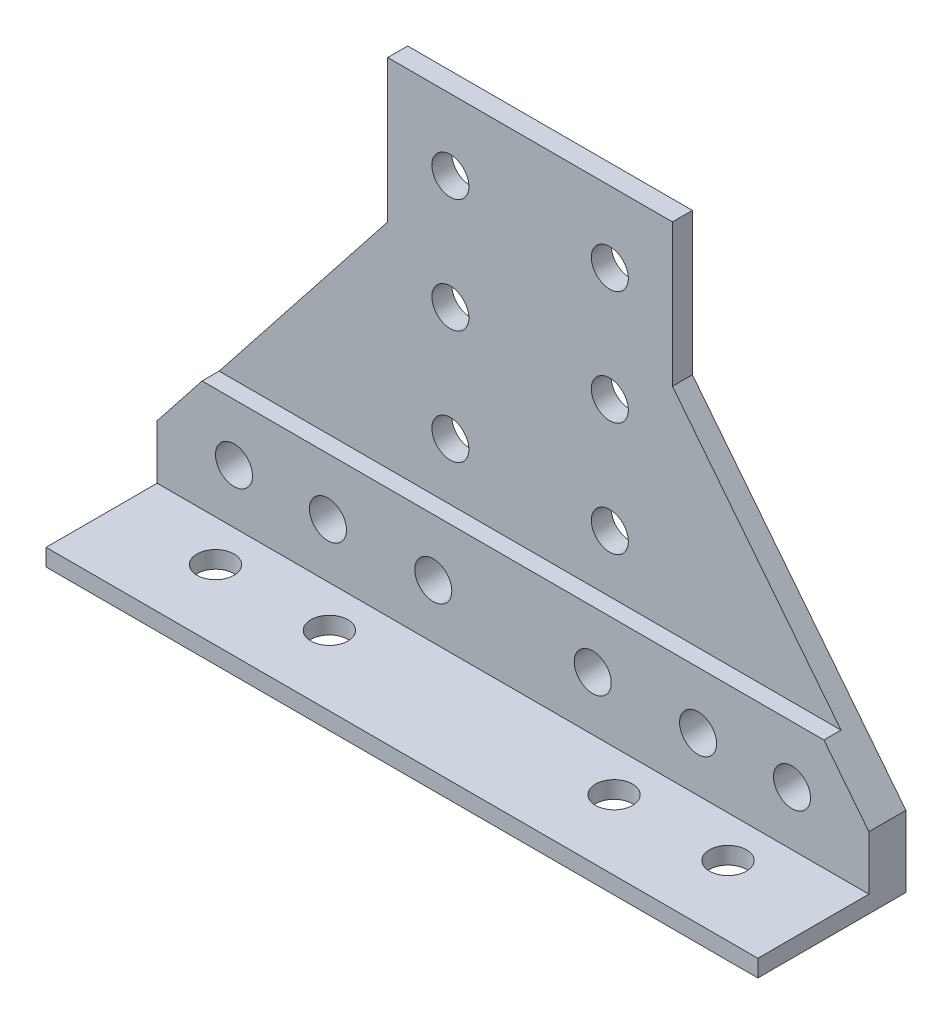
SolidWorks part; units mm, degrees
ref_plane "前视基准面" through (0, 0, 0) normal (0, 0, 1) x (1, 0, 0)
ref_plane "上视基准面" through (0, 0, 0) normal (0, 1, 0) x (1, 0, 0)
ref_plane "右视基准面" through (0, 0, 0) normal (1, 0, 0) x (0, 0, -1)
sketch "草图1" plane through (0, 0, 0) normal (0, 0, 1) x (1, 0, 0)
  line L1 (0, 0) -> (250, 0)
  line L2 (0, 0) -> (-250, 0)
  line L3 (-250, 0) -> (-250, 50)
  line L4 (250, 0) -> (250, 50)
  line L5 (0, 340) -> (100, 340)
  line L6 (0, 340) -> (-100, 340)
  line L7 (-100, 340) -> (-100, 240)
  line L8 (100, 340) -> (100, 240)
  line L9 (-100, 240) -> (-250, 50)
  line L10 (100, 240) -> (250, 50)
  dimension "D1" = 250
extrude "凸台-拉伸1" add sketch "草图1" along normal blind 14
sketch "草图2" plane through (0, 0, 14) normal (0, 0, 1) x (1, 0, 0)
  line L0 (-100, 290) -> (100, 290) construction
  line L1 (-100, 340) -> (-100, 240) construction
  line L2 (100, 240) -> (100, 340) construction
  line L3 (100, 340) -> (-100, 340) construction
  line L4 (0, 340) -> (0, 0) construction
  line L5 (-250, 50) -> (-250, 0) construction
  line L6 (-56, 340) -> (-56, 0) construction
  line L7 (-250, 0) -> (250, 0) construction
  dimension "D1" = 50
  dimension "D2" = 250
  dimension "D3" = 56
sketch "草图3" plane through (0, 0, 14) normal (0, 0, 1) x (1, 0, 0)
  line L0 (-100, 290) -> (100, 290) construction
  line L1 (-56, 340) -> (-56, 0) construction
  circle A0 centre (-56, 290) radius 13
extrude "切除-拉伸1" cut sketch "草图3" against normal through all
pattern_linear "阵列(线性)1" count 3 spacing 80 along (0, -1, 0) of "切除-拉伸1"
mirror "镜向1" about plane through (0, 0, 0) normal (1, 0, 0) of "阵列(线性)1", "切除-拉伸1"
sketch "草图6" plane through (0, 0, 14) normal (0, 0, 1) x (1, 0, 0)
  line L0 (-218.4211, 90) -> (218.4211, 90) construction
  line L1 (-100, 240) -> (-250, 50) construction
  line L2 (250, 50) -> (100, 240) construction
  line L3 (-250, 0) -> (250, 0) construction
  dimension "D1" = 90
extrude "凸台-拉伸2" add sketch "草图6" along normal blind 12
sketch "草图7" plane through (0, 0, 26) normal (0, 0, 1) x (1, 0, 0)
  line L0 (-250, 50) -> (250, 50) construction
  line L1 (-250, 50) -> (-250, 0) construction
  line L2 (250, 0) -> (250, 50) construction
  line L3 (-250, 0) -> (250, 0) construction
  line L4 (-130, 340) -> (-130, 0) construction
  line L5 (100, 340) -> (-100, 340) construction
  line L6 (-56, 340) -> (-56, 0) construction
  line L7 (-196, 340) -> (-196, 0) construction
  circle A0 centre (-56, 50) radius 13
  circle A1 centre (-130, 50) radius 13
  circle A2 centre (-196, 50) radius 13
  dimension "D1" = 50
  dimension "D2" = 74
  dimension "D3" = 140
extrude "切除-拉伸2" cut sketch "草图7" against normal through all
mirror "镜向2" about plane through (0, 0, 0) normal (1, 0, 0) of "切除-拉伸2"
sketch "草图8" plane through (0, 0, 26) normal (0, 0, 1) x (1, 0, 0)
  line L1 (-250, 0) -> (250, 0)
  line L2 (-250, 0) -> (-250, 12)
  line L3 (-250, 12) -> (250, 12)
  line L4 (250, 0) -> (250, 12)
extrude "凸台-拉伸5" add sketch "草图8" along normal blind 78
sketch "草图9" plane through (0, 0, 0) normal (0, -1, 0) x (1, 0, 0)
  line L0 (-250, 14) -> (250, 14) construction
  line L1 (-250, 104) -> (-250, 0) construction
  line L2 (250, 104) -> (250, 0) construction
  line L3 (-250, 0) -> (250, 0) construction
  line L4 (-250, 55) -> (250, 55) construction
  line L5 (-250, 104) -> (250, 104) construction
  line L6 (-180, 104) -> (-180, 0) construction
  line L7 (-100, 104) -> (-100, 0) construction
  circle A0 centre (-180, 55) radius 13
  circle A1 centre (-100, 55) radius 13
  dimension "D1" = 14
  dimension "D2" = 49
  dimension "D3" = 41
  dimension "D4" = 70
  dimension "D5" = 80
extrude "切除-拉伸3" cut sketch "草图9" against normal through all
mirror "镜向3" about plane through (0, 0, 0) normal (1, 0, 0) of "切除-拉伸3"
